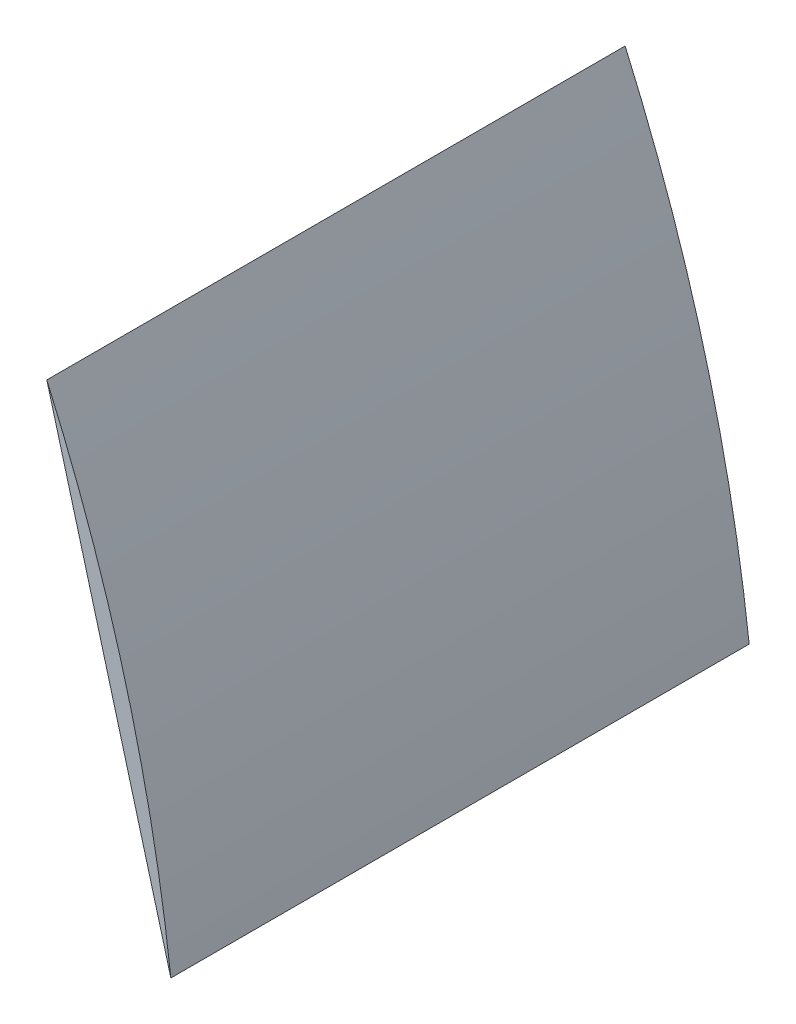
SolidWorks part; units mm, degrees
ref_plane "Front Plane" through (0, 0, 0) normal (0, 0, 1) x (1, 0, 0)
ref_plane "Top Plane" through (0, 0, 0) normal (0, 1, 0) x (1, 0, 0)
ref_plane "Right Plane" through (0, 0, 0) normal (1, 0, 0) x (0, 0, -1)
sketch "CurveSketch" plane through (0, 0, 0) normal (0, 0, 1) x (1, 0, 0)
  line L0 (14.4585, 16.0275) -> (12.9273, 21.6558)
  arc A0 (12.9273, 21.6558) -> (14.4585, 16.0275) centre (-5.137, 13.719) cw
  dimension "D1" = 19.731
extrude "CurveBoss" add sketch "CurveSketch" along normal blind 7.139
